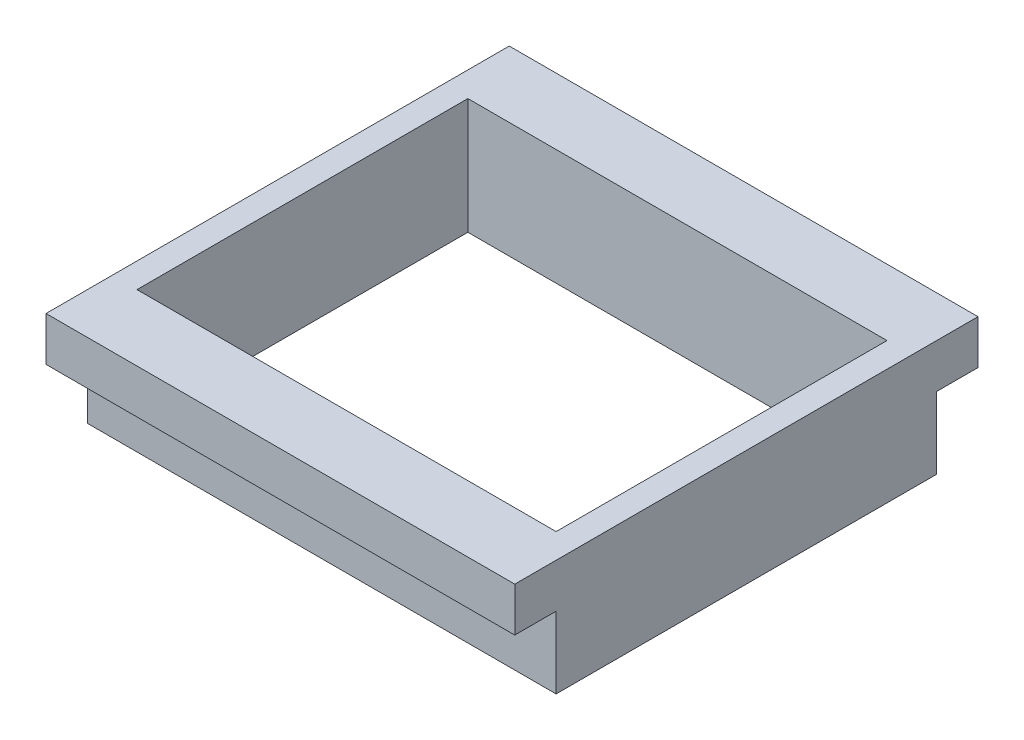
SolidWorks part; units mm, degrees
ref_plane "Спереди" through (0, 0, 0) normal (0, 0, 1) x (1, 0, 0)
ref_plane "Сверху" through (0, 0, 0) normal (0, 1, 0) x (1, 0, 0)
ref_plane "Справа" through (0, 0, 0) normal (1, 0, 0) x (0, 0, -1)
sketch "Эскиз1" plane through (0, 0, 0) normal (0, 1, 0) x (1, 0, 0)
  line L0 (21.25, -17.25) -> (-21.25, -17.25)
  line L1 (-21.25, -17.25) -> (-21.25, 17.25)
  line L3 (21.25, 17.25) -> (21.25, -17.25)
  line L5 (-21.25, 17.25) -> (21.25, 17.25)
  line L6 (-19, 15) -> (19, 15)
  line L8 (-19, 15) -> (-19, -15)
  line L9 (-19, -15) -> (19, -15)
  line L10 (19, -15) -> (19, 15)
  point P0 (0, 0)
extrude "Бобышка-Вытянуть1" add sketch "Эскиз1" along normal blind 6.5
ref_plane "Плоскость1" through (0, 6.5, 0) normal (0, 1, 0) x (1, 0, 0)
sketch "Эскиз2" plane through (0, 6.5, 0) normal (0, 1, 0) x (1, 0, 0)
  line L0 (-21.25, -21) -> (-21.25, 21)
  line L1 (-21.25, 21) -> (21.25, 21)
  line L2 (21.25, 21) -> (21.25, -21)
  line L3 (21.25, -21) -> (-21.25, -21)
  line L4 (-19, 15) -> (-19, -15)
  line L5 (-19, -15) -> (19, -15)
  line L6 (19, -15) -> (19, 15)
  line L7 (19, 15) -> (-19, 15)
  point P8 (0, 0)
  point P15 (0, 0)
  point P16 (0, 0)
extrude "Бобышка-Вытянуть2" add sketch "Эскиз2" along normal blind 4
